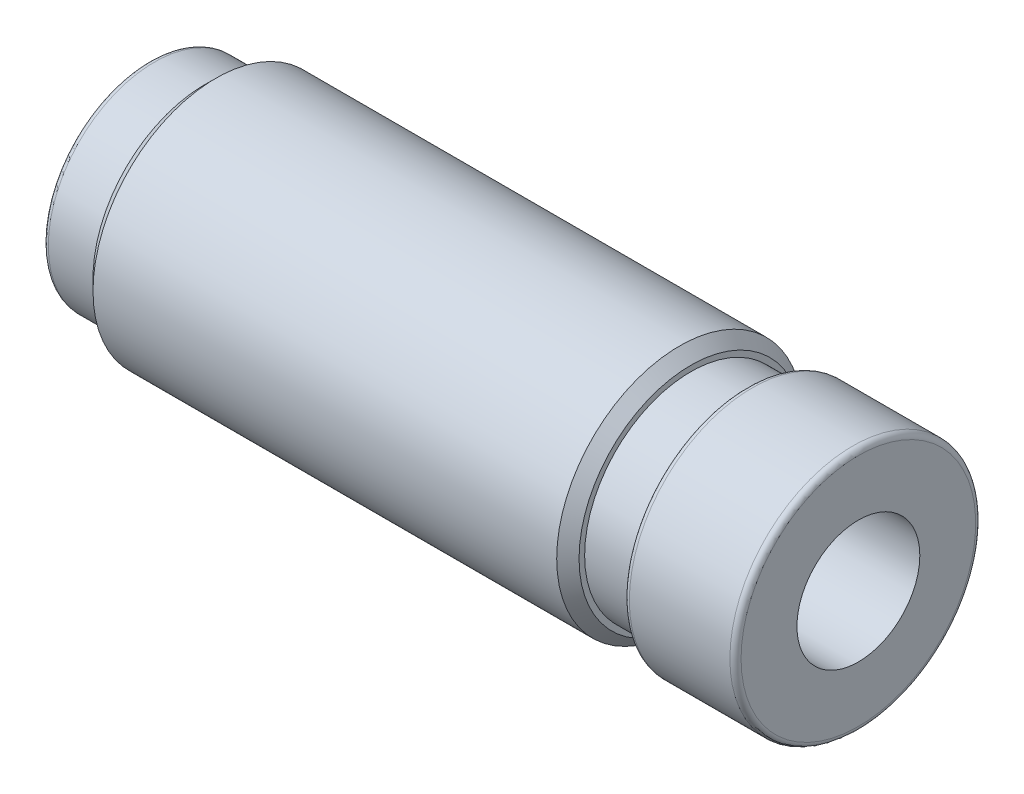
SolidWorks part; units mm, degrees
ref_plane "Plano frontal" through (0, 0, 0) normal (0, 0, 1) x (1, 0, 0)
ref_plane "Plano superior" through (0, 0, 0) normal (0, 1, 0) x (1, 0, 0)
ref_plane "Plano direito" through (0, 0, 0) normal (1, 0, 0) x (0, 0, -1)
sketch "Esboço1" plane through (0, 0, 0) normal (0, 0, 1) x (1, 0, 0)
  line L0 (0, 0) -> (63.5, 0)
  line L1 (63.5, 0) -> (63.5, 11)
  line L2 (63.5, 11) -> (53.5, 11)
  line L3 (53.5, 11) -> (53.5, 9.5)
  line L4 (53.5, 9.5) -> (48.5, 9.5)
  line L5 (48.5, 9.5) -> (48.5, 11)
  line L6 (48.5, 11) -> (5, 11)
  line L7 (5, 11) -> (5, 9.5)
  line L8 (5, 9.5) -> (0, 9.5)
  line L9 (0, 9.5) -> (0, 0)
  dimension "D1" = 5
  dimension "D2" = 10
  dimension "D3" = 5
  dimension "D4" = 63.5
  dimension "D5" = 11
  dimension "D6" = 1.5
  dimension "D7" = 9.5
  dimension "D8" = 9.5
revolve "Revolução1" add sketch "Esboço1" angle 360 about L0
cosmetic thread "Representação de rosca1" parameters "D1"=42.5, "D2"=19.252
hole_wizard "Furo1" positions "Esboço5" profile "Esboço6" legacy
sketch "Esboço5" plane through (63.5, 0, 0) normal (1, 0, 0) x (0, 0, -1)
  point P0 (0, 0)
sketch "Esboço6" plane through (63.5, 0, 0) normal (0, 1, 0) x (0, 0, -1)
  line L0 (0, 0) -> (0, 55.7)
  line L1 (0, 55.7) -> (5.5, 55.7)
  line L2 (5.5, 55.7) -> (5.5, 0)
  line L3 (5.5, 0) -> (0, 0)
  line L4 (0, 110) -> (0, -10) construction
  dimension "Diameter" = 11
  dimension "Depth" = 55.7
hole_wizard "Furo2" positions "Esboço7" profile "Esboço8" legacy
sketch "Esboço7" plane through (0, 0, 0) normal (-1, 0, 0) x (0, 0, 1)
  point P0 (0, 0)
sketch "Esboço8" plane through (0, 0, 0) normal (0, 1, 0) x (0, 0, 1)
  line L0 (0, 0) -> (0, 8)
  line L1 (0, 8) -> (4.7, 8)
  line L2 (4.7, 8) -> (4.7, 0)
  line L3 (4.7, 0) -> (0, 0)
  line L4 (0, 110) -> (0, -10) construction
  dimension "Diameter" = 9.4
  dimension "Depth" = 8
fillet "Filete2" radius 0.5 2 edges at (53.5, 0, 11) (63.5, 0, 11)
fillet "Filete3" radius 0.5 1 edges at (0, 0, 4.7)
fillet "Filete4" radius 0.5 1 edges at (0, 0, 9.5)
chamfer "Chanfro1" distance 1 angle 45 2 edges at (48.5, 0, 11) (5, 0, 11)
